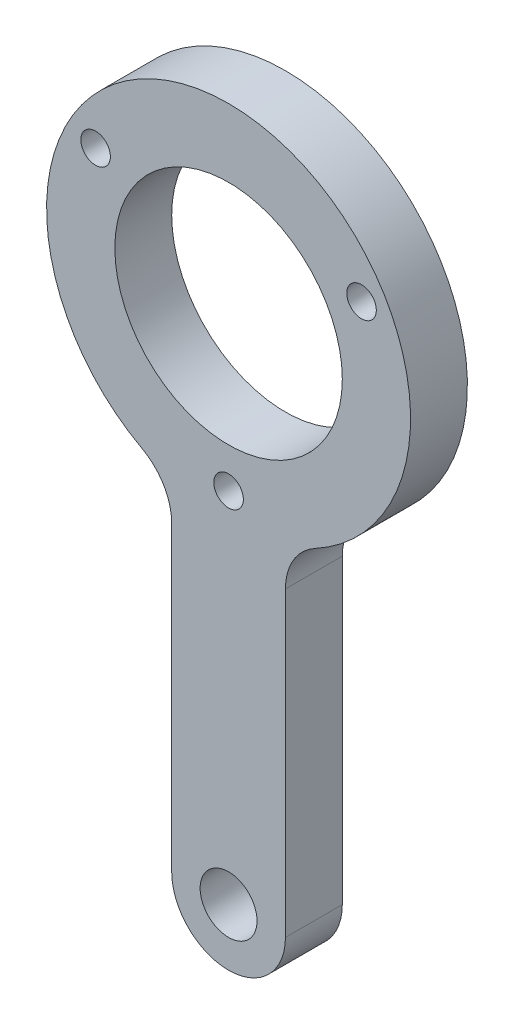
SolidWorks part; units mm, degrees
material "Thornel Mat VMA"
ref_plane "前视基准面" through (0, 0, 0) normal (0, 0, 1) x (1, 0, 0)
ref_plane "上视基准面" through (0, 0, 0) normal (0, 1, 0) x (1, 0, 0)
ref_plane "右视基准面" through (0, 0, 0) normal (1, 0, 0) x (0, 0, -1)
sketch "草图1" plane through (0, 0, 0) normal (0, 0, 1) x (1, 0, 0)
  line L0 (0, 0) -> (0, -45) construction
  line L1 (5, -8.0777) -> (5, -45)
  line L2 (-5, -8.0777) -> (-5, -45)
  arc A0 (5, -8.0777) -> (-5, -8.0777) centre (0, 0) ccw
  arc A2 (-5, -45) -> (5, -45) centre (0, -45) ccw
  point P3 (0, -25)
  dimension "D1" = 45
  dimension "D2" = 19
  dimension "D3" = 5
extrude "凸台-拉伸1" add sketch "草图1" along normal blind 5
sketch "草图3" plane through (0, 0, 5) normal (0, 0, 1) x (1, 0, 0)
  circle A0 centre (0, -45) radius 2.5
  dimension "D1" = 5
extrude "切除-拉伸1" cut sketch "草图3" against normal blind 24
sketch "草图4" plane through (0, 0, 5) normal (0, 0, 1) x (1, 0, 0)
  circle A0 centre (0, 0) radius 6.25 construction
  circle A1 centre (0, 6.25) radius 1.525
  circle A2 centre (0, -6.25) radius 1.525
  dimension "D1" = 12.5
  dimension "D2" = 3.05
extrude "切除-拉伸2" cut sketch "草图4" against normal blind 5
sketch "草图5" plane through (0, 0, 5) normal (0, 0, 1) x (1, 0, 0)
  circle A0 centre (0, 0) radius 2.5
  dimension "D1" = 5
extrude "切除-拉伸3" cut sketch "草图5" against normal blind 5
fillet "圆角1" radius 5 2 edges at (5, -8.0777, 2.5) (-5, -8.0777, 2.5)
sketch "草图6" plane through (0, 0, 5) normal (0, 0, 1) x (1, 0, 0)
  circle A0 centre (0, 0) radius 13.5 construction
  circle A1 centre (0, -13.5) radius 1.3
  circle A2 centre (-11.6913, 6.75) radius 1.3
  circle A3 centre (11.6913, 6.75) radius 1.3
  circle A4 centre (0, 0) radius 16
  circle A5 centre (0, 0) radius 10
  point P11 (0, 0)
  dimension "D2" = 27
  dimension "D3" = 2.6
  dimension "D4" = 32
  dimension "D5" = 20
  dimension "D1" = 3
extrude "切除-拉伸4" cut sketch "草图6" against normal blind 10 contours A1 | A5
sketch "草图7" plane through (0, 0, 5) normal (0, 0, 1) x (1, 0, 0)
  circle A1 centre (0, 0) radius 10
  circle A2 centre (0, 0) radius 10
  circle A3 centre (0, 0) radius 16
  circle A4 centre (0, 0) radius 16
  circle A5 centre (11.6913, 6.75) radius 1.3
  circle A6 centre (11.6913, 6.75) radius 1.3
  circle A7 centre (-11.6913, 6.75) radius 1.3
  circle A8 centre (-11.6913, 6.75) radius 1.3
  circle A9 centre (0, -13.5) radius 1.3
  circle A10 centre (0, -13.5) radius 1.3
  dimension "D1" = 0
  dimension "D2" = 0
  dimension "D3" = 0
  dimension "D4" = 0
  dimension "D5" = 0
extrude "凸台-拉伸2" add sketch "草图7" against normal blind 5
fillet "圆角2" radius 5 2 edges at (-5, -15.1987, 2.5) (5, -15.1987, 2.5)
